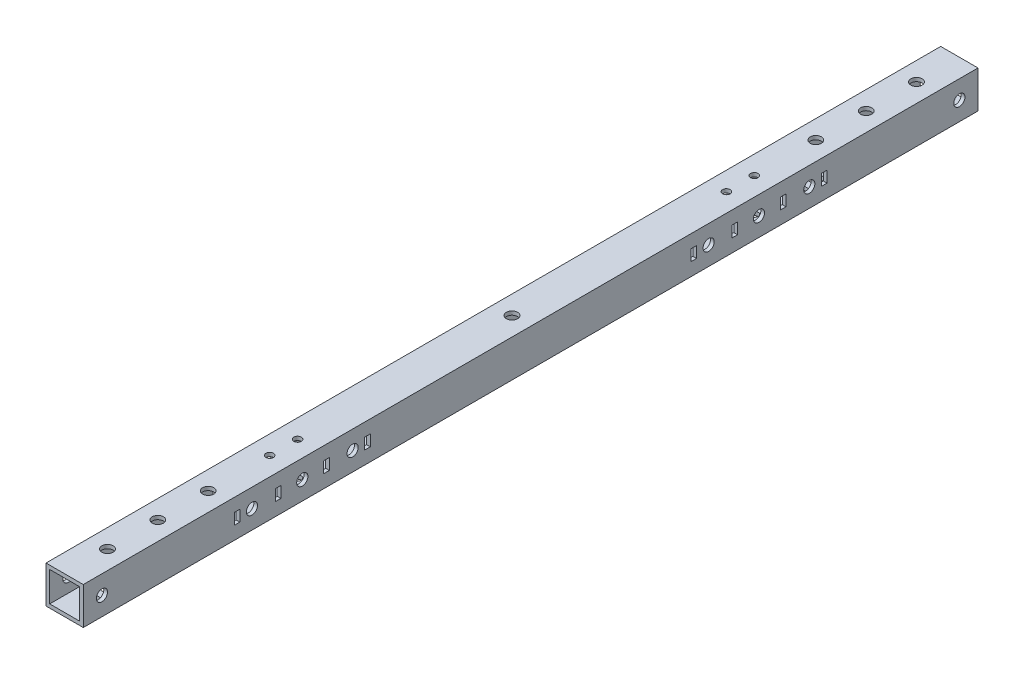
SolidWorks part; units mm, degrees
ref_plane "前视基准面" through (0, 0, 0) normal (0, 0, 1) x (1, 0, 0)
ref_plane "上视基准面" through (0, 0, 0) normal (0, 1, 0) x (1, 0, 0)
ref_plane "右视基准面" through (0, 0, 0) normal (1, 0, 0) x (0, 0, -1)
sketch "草图1" plane through (0, 0, 0) normal (0, 0, 1) x (1, 0, 0)
  line L1 (-10, 10) -> (10, 10)
  line L2 (-10, 10) -> (-10, -10)
  line L3 (-10, -10) -> (10, -10)
  line L4 (10, 10) -> (10, -10)
  line L5 (-10, 10) -> (10, -10) construction
  line L6 (-10, -10) -> (10, 10) construction
  line L7 (-8, 8) -> (8, 8)
  line L8 (-8, 8) -> (-8, -8)
  line L9 (-8, -8) -> (8, -8)
  line L10 (8, 8) -> (8, -8)
  line L11 (-8, 8) -> (8, -8) construction
  line L12 (-8, -8) -> (8, 8) construction
  point P0 (0, 0)
  point P5 (0, 0)
  dimension "D1" = 2
  dimension "D2" = 20
  dimension "D3" = 20
  dimension "D4" = 2
extrude "凸台-拉伸1" add sketch "草图1" along normal blind 480
sketch "草图2" plane through (0, 10, 0) normal (0, 1, 0) x (1, 0, 0)
  line L0 (-128.3396, -240) -> (113.5122, -240) construction
  line L1 (10, -480) -> (-10, -480) construction
  line L2 (10, 0) -> (-10, 0) construction
  circle A0 centre (0, -50) radius 3
  circle A1 centre (0, -430) radius 3
  dimension "D1" = 6
  dimension "D2" = 380
extrude "切除-拉伸1" cut sketch "草图2" against normal blind 450
sketch "草图3" plane through (0, -10, 0) normal (0, -1, 0) x (1, 0, 0)
  line L0 (-157.3305, 240) -> (219.0911, 240) construction
  line L1 (-10, 480) -> (10, 480) construction
  line L2 (-43.9471, 50) -> (88.1026, 50) construction
  line L3 (0, 107.4521) -> (0, -3.5248) construction
  line L4 (-3, 64.5) -> (3, 64.5) construction
  line L5 (-3, 64.5) -> (-3, 61.5) construction
  line L6 (-3, 61.5) -> (3, 61.5) construction
  line L7 (3, 64.5) -> (3, 61.5) construction
  line L8 (-3, 64.5) -> (3, 61.5) construction
  line L9 (-3, 61.5) -> (3, 64.5) construction
  line L10 (-3, 86.5) -> (3, 86.5) construction
  line L11 (-3, 86.5) -> (-3, 83.5) construction
  line L12 (-3, 83.5) -> (3, 83.5) construction
  line L13 (3, 86.5) -> (3, 83.5) construction
  line L14 (-3, 86.5) -> (3, 83.5) construction
  line L15 (-3, 83.5) -> (3, 86.5) construction
  line L16 (-3, 16.5) -> (3, 13.5) construction
  line L17 (-3, 13.5) -> (3, 16.5) construction
  line L18 (-3, 38.5) -> (3, 35.5) construction
  line L19 (-3, 35.5) -> (3, 38.5) construction
  line L20 (0, -7.4521) -> (0, 103.5248) construction
  line L21 (3, 13.5) -> (3, 16.5) construction
  line L22 (-3, 16.5) -> (3, 16.5) construction
  line L23 (-3, 13.5) -> (-3, 16.5) construction
  line L24 (-3, 13.5) -> (3, 13.5) construction
  line L25 (3, 35.5) -> (3, 38.5) construction
  line L26 (-3, 38.5) -> (3, 38.5) construction
  line L27 (-3, 35.5) -> (-3, 38.5) construction
  line L28 (-3, 35.5) -> (3, 35.5) construction
  line L29 (-3, 444.5) -> (3, 441.5) construction
  line L30 (-3, 441.5) -> (3, 444.5) construction
  line L31 (-3, 466.5) -> (3, 463.5) construction
  line L32 (-3, 463.5) -> (3, 466.5) construction
  line L33 (-3, 396.5) -> (3, 393.5) construction
  line L34 (-3, 393.5) -> (3, 396.5) construction
  line L35 (-3, 418.5) -> (3, 415.5) construction
  line L36 (-3, 415.5) -> (3, 418.5) construction
  line L37 (-3, 444.5) -> (3, 444.5) construction
  line L38 (-3, 444.5) -> (-3, 441.5) construction
  line L39 (-3, 441.5) -> (3, 441.5) construction
  line L40 (3, 444.5) -> (3, 441.5) construction
  line L41 (-3, 466.5) -> (3, 466.5) construction
  line L42 (-3, 466.5) -> (-3, 463.5) construction
  line L43 (-3, 463.5) -> (3, 463.5) construction
  line L44 (3, 466.5) -> (3, 463.5) construction
  line L45 (3, 393.5) -> (3, 396.5) construction
  line L46 (-3, 396.5) -> (3, 396.5) construction
  line L47 (-3, 393.5) -> (-3, 396.5) construction
  line L48 (-3, 393.5) -> (3, 393.5) construction
  line L49 (3, 415.5) -> (3, 418.5) construction
  line L50 (-3, 418.5) -> (3, 418.5) construction
  line L51 (-3, 415.5) -> (-3, 418.5) construction
  line L52 (-3, 415.5) -> (3, 415.5) construction
  circle A0 centre (0, 77) radius 3
  circle A1 centre (0, 23) radius 3
  circle A2 centre (0, 457) radius 3
  circle A3 centre (0, 403) radius 3
  point P6 (0, 50)
  point P10 (0, 63)
  point P15 (0, 85)
  point P38 (0, 15)
  point P39 (0, 37)
  point P60 (0, 443)
  point P61 (0, 465)
  point P62 (0, 395)
  point P63 (0, 417)
  point P64 (0, 430)
  dimension "D2" = 3
  dimension "D4" = 6
  dimension "D1" = 240
  dimension "D3" = 3
  dimension "D5" = 6
  dimension "D6" = 6
  dimension "D7" = 11.5
  dimension "D8" = 12.5
  dimension "D9" = 8
extrude "切除-拉伸2" cut sketch "草图3" against normal blind 10
sketch "草图4" plane through (0, -10, 0) normal (0, -1, 0) x (1, 0, 0)
  circle A0 centre (0, 403) radius 3 construction
  circle A1 centre (0, 457) radius 3 construction
  circle A2 centre (0, 403) radius 3
  circle A3 centre (0, 457) radius 3
  circle A4 centre (0, 77) radius 3 construction
  circle A5 centre (0, 23) radius 3 construction
  circle A6 centre (0, 77) radius 3
  circle A7 centre (0, 23) radius 3
extrude "切除-拉伸3" cut sketch "草图4" against normal blind 85
sketch "草图5" plane through (10, 0, 0) normal (1, 0, 0) x (0, 0, -1)
  line L0 (-240, 146.9504) -> (-240, -170.539) construction
  line L1 (-541.2324, 0) -> (91.8337, 0) construction
  line L2 (-362.5, 86.9864) -> (-362.5, -76.8926) construction
  line L3 (-326, -3) -> (-329, 3) construction
  line L4 (-377, 3) -> (-374, 3) construction
  line L5 (-377, 3) -> (-377, -3) construction
  line L6 (-377, -3) -> (-374, -3) construction
  line L7 (-374, 3) -> (-374, -3) construction
  line L8 (-377, 3) -> (-374, -3) construction
  line L9 (-377, -3) -> (-374, 3) construction
  line L10 (-399, 3) -> (-396, 3) construction
  line L11 (-399, 3) -> (-399, -3) construction
  line L12 (-399, -3) -> (-396, -3) construction
  line L13 (-396, 3) -> (-396, -3) construction
  line L14 (-399, 3) -> (-396, -3) construction
  line L15 (-399, -3) -> (-396, 3) construction
  line L16 (-326, 3) -> (-329, -3) construction
  line L17 (-348, -3) -> (-351, 3) construction
  line L18 (-348, 3) -> (-351, -3) construction
  line L19 (-329, 3) -> (-329, -3) construction
  line L20 (-326, -3) -> (-329, -3) construction
  line L21 (-326, 3) -> (-326, -3) construction
  line L22 (-326, 3) -> (-329, 3) construction
  line L23 (-351, 3) -> (-351, -3) construction
  line L24 (-348, -3) -> (-351, -3) construction
  line L25 (-348, 3) -> (-348, -3) construction
  line L26 (-348, 3) -> (-351, 3) construction
  line L27 (-132, 3) -> (-129, -3) construction
  line L28 (-132, -3) -> (-129, 3) construction
  line L29 (-154, 3) -> (-151, -3) construction
  line L30 (-81, -3) -> (-84, 3) construction
  line L31 (-81, 3) -> (-84, -3) construction
  line L32 (-103, -3) -> (-106, 3) construction
  line L33 (-103, 3) -> (-106, -3) construction
  line L34 (-154, -3) -> (-151, 3) construction
  line L35 (-117.5, 86.9864) -> (-117.5, -76.8926) construction
  line L36 (61.2324, 0) -> (-571.8337, 0) construction
  line L37 (-132, 3) -> (-129, 3) construction
  line L38 (-132, 3) -> (-132, -3) construction
  line L39 (-132, -3) -> (-129, -3) construction
  line L40 (-129, 3) -> (-129, -3) construction
  line L41 (-154, 3) -> (-151, 3) construction
  line L42 (-154, 3) -> (-154, -3) construction
  line L43 (-154, -3) -> (-151, -3) construction
  line L44 (-151, 3) -> (-151, -3) construction
  line L45 (-84, 3) -> (-84, -3) construction
  line L46 (-81, -3) -> (-84, -3) construction
  line L47 (-81, 3) -> (-81, -3) construction
  line L48 (-81, 3) -> (-84, 3) construction
  line L49 (-106, 3) -> (-106, -3) construction
  line L50 (-103, -3) -> (-106, -3) construction
  line L51 (-103, 3) -> (-103, -3) construction
  line L52 (-103, 3) -> (-106, 3) construction
  circle A0 centre (-362.5, 0) radius 3
  circle A1 centre (-389.5, 0) radius 3
  circle A2 centre (-335.5, 0) radius 3
  circle A3 centre (-144.5, 0) radius 3
  circle A4 centre (-90.5, 0) radius 3
  circle A5 centre (-117.5, 0) radius 3
  point P9 (-375.5, 0)
  point P14 (-397.5, 0)
  point P34 (-327.5, 0)
  point P35 (-349.5, 0)
  point P62 (-130.5, 0)
  point P63 (-152.5, 0)
  point P67 (-82.5, 0)
  point P68 (-104.5, 0)
  dimension "D3" = 6
  dimension "D13" = 6
  dimension "D1" = 240
  dimension "D2" = 122.5
  dimension "D4" = 3
  dimension "D5" = 6
  dimension "D6" = 3
  dimension "D7" = 6
  dimension "D14" = 11.5
  dimension "D15" = 14
  dimension "D16" = 8
extrude "切除-拉伸4" cut sketch "草图5" against normal blind 10
sketch "草图6" plane through (10, 0, 0) normal (1, 0, 0) x (0, 0, -1)
  circle A0 centre (-335.5, 0) radius 3 construction
  circle A1 centre (-362.5, 0) radius 3 construction
  circle A2 centre (-389.5, 0) radius 3 construction
  circle A3 centre (-335.5, 0) radius 3
  circle A4 centre (-362.5, 0) radius 3
  circle A5 centre (-389.5, 0) radius 3
  circle A6 centre (-90.5, 0) radius 3 construction
  circle A7 centre (-117.5, 0) radius 3 construction
  circle A8 centre (-144.5, 0) radius 3 construction
  circle A9 centre (-90.5, 0) radius 3
  circle A10 centre (-117.5, 0) radius 3
  circle A11 centre (-144.5, 0) radius 3
extrude "切除-拉伸5" cut sketch "草图6" against normal blind 27
sketch "草图8" plane through (-10, 0, 0) normal (-1, 0, 0) x (0, 0, 1)
  line L0 (-36.7968, 0) -> (516.7968, 0) construction
  line L2 (0, 10) -> (0, -10) construction
  line L3 (480, 10) -> (480, -10) construction
  circle A0 centre (10, 0) radius 3
  circle A2 centre (470, 0) radius 3
  dimension "D3" = 6
  dimension "D5" = 6
  dimension "D4" = 10
  dimension "D6" = 10
extrude "切除-拉伸6" cut sketch "草图8" against normal blind 54.24
sketch "草图9" plane through (0, -10, 0) normal (0, -1, 0) x (1, 0, 0)
  line L0 (-10, 0) -> (10, 0) construction
  circle A0 centre (0, 240) radius 3
  dimension "D1" = 6
  dimension "D2" = 240
extrude "切除-拉伸7" cut sketch "草图9" against normal blind 54.24
sketch "草图10" plane through (0, 10, 0) normal (0, 1, 0) x (1, 0, 0)
  line L4 (3, -13.5) -> (-3, -13.5)
  line L5 (3, -16.5) -> (3, -13.5)
  line L6 (-3, -16.5) -> (3, -16.5)
  line L7 (-3, -13.5) -> (-3, -16.5)
  line L8 (3, -13.5) -> (-3, -13.5)
  line L9 (3, -16.5) -> (3, -13.5)
  line L10 (-3, -16.5) -> (3, -16.5)
  line L11 (-3, -13.5) -> (-3, -16.5)
  line L12 (3, -35.5) -> (-3, -35.5)
  line L13 (3, -38.5) -> (3, -35.5)
  line L14 (-3, -38.5) -> (3, -38.5)
  line L15 (-3, -35.5) -> (-3, -38.5)
  line L16 (3, -35.5) -> (-3, -35.5)
  line L17 (3, -38.5) -> (3, -35.5)
  line L18 (-3, -38.5) -> (3, -38.5)
  line L19 (-3, -35.5) -> (-3, -38.5)
  line L20 (3, -83.5) -> (-3, -83.5)
  line L21 (3, -86.5) -> (3, -83.5)
  line L22 (-3, -86.5) -> (3, -86.5)
  line L23 (-3, -83.5) -> (-3, -86.5)
  line L24 (3, -83.5) -> (-3, -83.5)
  line L25 (3, -86.5) -> (3, -83.5)
  line L26 (-3, -86.5) -> (3, -86.5)
  line L27 (-3, -83.5) -> (-3, -86.5)
  line L28 (3, -61.5) -> (-3, -61.5)
  line L29 (3, -64.5) -> (3, -61.5)
  line L30 (-3, -64.5) -> (3, -64.5)
  line L31 (-3, -61.5) -> (-3, -64.5)
  line L32 (3, -61.5) -> (-3, -61.5)
  line L33 (3, -64.5) -> (3, -61.5)
  line L34 (-3, -64.5) -> (3, -64.5)
  line L35 (-3, -61.5) -> (-3, -64.5)
  line L36 (3, -463.5) -> (-3, -463.5)
  line L37 (3, -466.5) -> (3, -463.5)
  line L38 (-3, -466.5) -> (3, -466.5)
  line L39 (-3, -463.5) -> (-3, -466.5)
  line L40 (3, -463.5) -> (-3, -463.5)
  line L41 (3, -466.5) -> (3, -463.5)
  line L42 (-3, -466.5) -> (3, -466.5)
  line L43 (-3, -463.5) -> (-3, -466.5)
  line L44 (3, -441.5) -> (-3, -441.5)
  line L45 (3, -444.5) -> (3, -441.5)
  line L46 (-3, -444.5) -> (3, -444.5)
  line L47 (-3, -441.5) -> (-3, -444.5)
  line L48 (3, -441.5) -> (-3, -441.5)
  line L49 (3, -444.5) -> (3, -441.5)
  line L50 (-3, -444.5) -> (3, -444.5)
  line L51 (-3, -441.5) -> (-3, -444.5)
  line L52 (3, -415.5) -> (-3, -415.5)
  line L53 (3, -418.5) -> (3, -415.5)
  line L54 (-3, -418.5) -> (3, -418.5)
  line L55 (-3, -415.5) -> (-3, -418.5)
  line L56 (3, -415.5) -> (-3, -415.5)
  line L57 (3, -418.5) -> (3, -415.5)
  line L58 (-3, -418.5) -> (3, -418.5)
  line L59 (-3, -415.5) -> (-3, -418.5)
  line L60 (3, -393.5) -> (-3, -393.5)
  line L61 (3, -396.5) -> (3, -393.5)
  line L62 (-3, -396.5) -> (3, -396.5)
  line L63 (-3, -393.5) -> (-3, -396.5)
  line L64 (3, -393.5) -> (-3, -393.5)
  line L65 (3, -396.5) -> (3, -393.5)
  line L66 (-3, -396.5) -> (3, -396.5)
  line L67 (-3, -393.5) -> (-3, -396.5)
  dimension "D1" = 0
  dimension "D2" = 0
  dimension "D3" = 0
  dimension "D4" = 0
  dimension "D5" = 0
  dimension "D6" = 0
  dimension "D7" = 0
  dimension "D8" = 0
extrude "切除-拉伸8" cut sketch "草图10" against normal blind 20 from offset 10 offset against normal yes
sketch "草图11" plane through (-10, 0, 0) normal (-1, 0, 0) x (0, 0, 1)
  line L0 (323.243, 0) -> (403.023, 0) construction
  line L1 (362.5, 0) -> (362.5, 7.7593) construction
  line L2 (348, 3) -> (351, 3)
  line L3 (348, 3) -> (348, -3)
  line L4 (348, -3) -> (351, -3)
  line L5 (351, 3) -> (351, -3)
  line L6 (348, 3) -> (351, -3) construction
  line L7 (348, -3) -> (351, 3) construction
  line L8 (326, 3) -> (329, 3)
  line L9 (326, 3) -> (326, -3)
  line L10 (326, -3) -> (329, -3)
  line L11 (329, 3) -> (329, -3)
  line L12 (326, 3) -> (329, -3) construction
  line L13 (326, -3) -> (329, 3) construction
  line L14 (377, -3) -> (374, -3)
  line L15 (374, 3) -> (374, -3)
  line L16 (377, 3) -> (374, 3)
  line L17 (377, 3) -> (377, -3)
  line L18 (399, -3) -> (396, -3)
  line L19 (396, 3) -> (396, -3)
  line L20 (399, 3) -> (396, 3)
  line L21 (399, 3) -> (399, -3)
  line L22 (240, 32.5073) -> (240, -23.9662) construction
  line L23 (81, 3) -> (81, -3)
  line L24 (81, 3) -> (84, 3)
  line L25 (84, 3) -> (84, -3)
  line L26 (81, -3) -> (84, -3)
  line L27 (103, -3) -> (106, -3)
  line L28 (106, 3) -> (106, -3)
  line L29 (103, 3) -> (106, 3)
  line L30 (103, 3) -> (103, -3)
  line L31 (132, -3) -> (129, -3)
  line L32 (129, 3) -> (129, -3)
  line L33 (132, 3) -> (129, 3)
  line L34 (132, 3) -> (132, -3)
  line L35 (154, -3) -> (151, -3)
  line L36 (151, 3) -> (151, -3)
  line L37 (154, 3) -> (151, 3)
  line L38 (154, 3) -> (154, -3)
  circle A0 centre (335.5, 0) radius 3 construction
  circle A1 centre (144.5, 0) radius 3 construction
  point P3 (349.5, 0)
  point P8 (327.5, 0)
  dimension "D6" = 12.5
  dimension "D1" = 6
  dimension "D2" = 6
  dimension "D3" = 3
  dimension "D4" = 3
  dimension "D5" = 6.5
extrude "切除-拉伸9" cut sketch "草图11" against normal blind 20 from offset 10 offset against normal yes
sketch "草图12" plane through (0, 10, 0) normal (0, 1, 0) x (1, 0, 0)
  circle A0 centre (0, -355) radius 2
  circle A1 centre (0, -370) radius 2
  circle A2 centre (0, -110) radius 2
  circle A3 centre (0, -125) radius 2
  dimension "D1" = 4
  dimension "D2" = 4
  dimension "D3" = 4
  dimension "D4" = 4
extrude "切除-拉伸10" cut sketch "草图12" against normal blind 20
